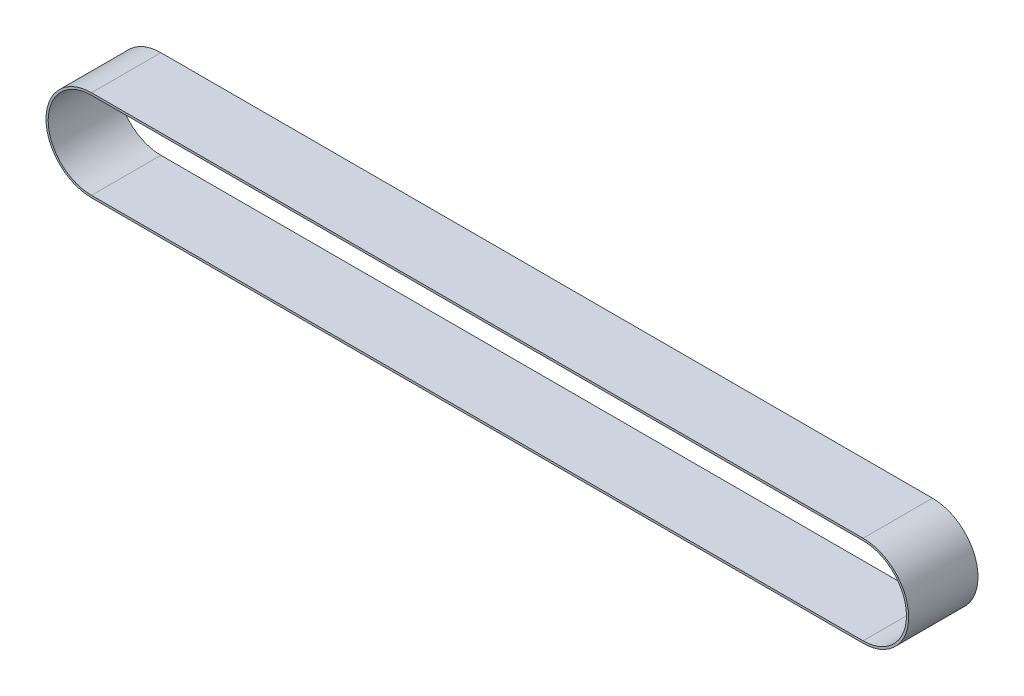
SolidWorks part; units mm, degrees
material "POLYURETHANE (11671)"
ref_plane "Front Plane" through (0, 0, 0) normal (0, 0, 1) x (1, 0, 0)
ref_plane "Top Plane" through (0, 0, 0) normal (0, 1, 0) x (1, 0, 0)
ref_plane "Right Plane" through (0, 0, 0) normal (1, 0, 0) x (0, 0, -1)
sketch "Sketch1" plane through (0, 0, 0) normal (0, 0, 1) x (1, 0, 0)
  line L0 (0, 0) -> (565.15, 0) construction
  line L1 (0, 31.75) -> (565.15, 31.75)
  line L2 (0, -31.75) -> (565.15, -31.75)
  line L3 (0, 0) -> (565.15, 0) construction
  line L4 (0, 33.3375) -> (565.15, 33.3375)
  line L5 (0, -33.3375) -> (565.15, -33.3375)
  arc A0 (0, 31.75) -> (0, -31.75) centre (0, 0) ccw
  arc A1 (565.15, -31.75) -> (565.15, 31.75) centre (565.15, 0) ccw
  arc A2 (0, 33.3375) -> (0, -33.3375) centre (0, 0) ccw
  arc A3 (565.15, -33.3375) -> (565.15, 33.3375) centre (565.15, 0) ccw
  point P3 (282.575, 0)
  point P10 (282.575, 0)
  dimension "D2" = 63.5
  dimension "D3" = 66.675
  dimension "D1" = 565.15
extrude "Boss-Extrude1" add sketch "Sketch1" along normal blind 50.8
